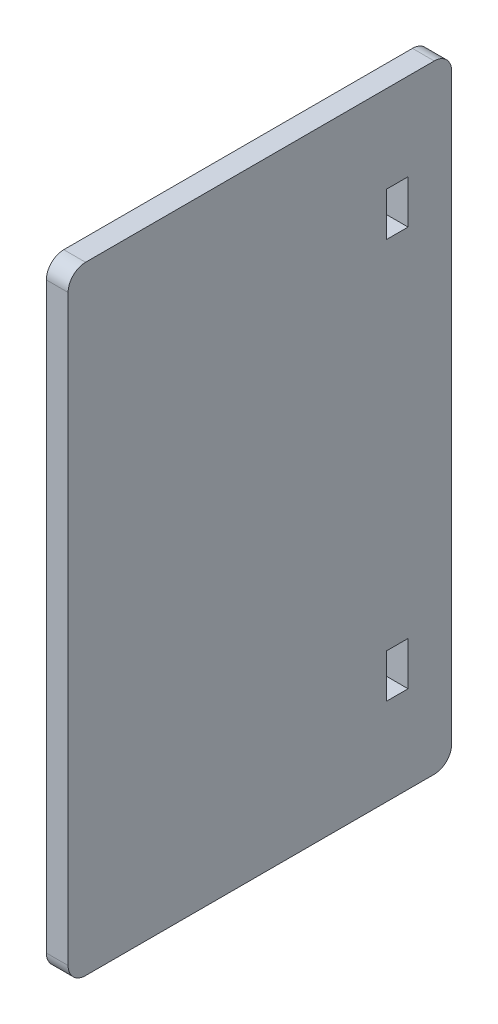
SolidWorks part; units mm, degrees
material "Acrylic (Medium-high impact)"
ref_plane "Front Plane" through (0, 0, 0) normal (0, 0, 1) x (1, 0, 0)
ref_plane "Top Plane" through (0, 0, 0) normal (0, 1, 0) x (1, 0, 0)
ref_plane "Right Plane" through (0, 0, 0) normal (1, 0, 0) x (0, 0, -1)
sketch "Sketch1" plane through (0, 0, 0) normal (1, 0, 0) x (0, 0, -1)
  line L1 (27.9375, -45) -> (-27.9375, -45)
  line L2 (27.9375, -45) -> (27.9375, 45)
  line L3 (27.9375, 45) -> (-27.9375, 45)
  line L4 (-27.9375, -45) -> (-27.9375, 45)
  line L5 (27.9375, -45) -> (-27.9375, 45) construction
  line L6 (27.9375, 45) -> (-27.9375, -45) construction
  point P0 (0, 0)
  dimension "D1" = 55.875
  dimension "D2" = 90
extrude "Boss-Extrude1" add sketch "Sketch1" along normal blind 3.175
sketch "Sketch2" plane through (3.175, 0, 0) normal (1, 0, 0) x (0, 0, -1)
  line L0 (27.9375, -45) -> (27.9375, 45) construction
  line L1 (18.4125, 32.3) -> (21.5875, 32.3)
  line L2 (18.4125, 32.3) -> (18.4125, 25.95)
  line L3 (18.4125, 25.95) -> (21.5875, 25.95)
  line L4 (21.5875, 32.3) -> (21.5875, 25.95)
  line L5 (18.4125, -25.95) -> (21.5875, -25.95)
  line L6 (18.4125, -25.95) -> (18.4125, -32.3)
  line L7 (18.4125, -32.3) -> (21.5875, -32.3)
  line L8 (21.5875, -25.95) -> (21.5875, -32.3)
  line L9 (-27.9375, -45) -> (27.9375, -45) construction
  line L10 (27.9375, 45) -> (-27.9375, 45) construction
  dimension "D1" = 3.175
  dimension "D2" = 3.175
  dimension "D3" = 6.35
  dimension "D4" = 6.35
  dimension "D5" = 6.35
  dimension "D6" = 6.35
  dimension "D7" = 12.7
  dimension "D8" = 12.7
extrude "Cut-Extrude1" cut sketch "Sketch2" against normal through all
fillet "Fillet1" radius 2.54 4 edges at (1.5875, -45, 27.9375) (1.5875, -45, -27.9375) (1.5875, 45, -27.9375) (1.5875, 45, 27.9375)
